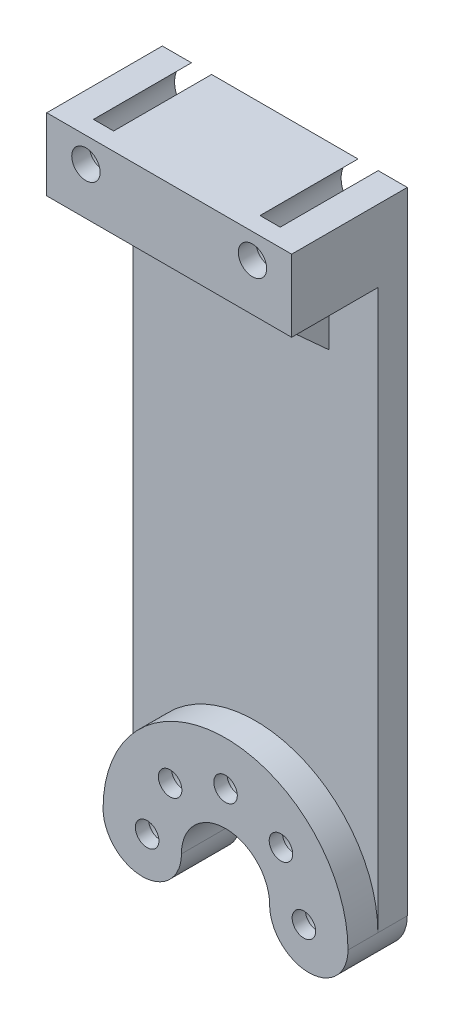
SolidWorks part; units mm, degrees
ref_plane "Plano frontal" through (0, 0, 0) normal (0, 0, 1) x (1, 0, 0)
ref_plane "Plano superior" through (0, 0, 0) normal (0, 1, 0) x (1, 0, 0)
ref_plane "Plano direito" through (0, 0, 0) normal (1, 0, 0) x (0, 0, -1)
sketch "Esboço1" plane through (0, 0, 0) normal (0, 0, 1) x (1, 0, 0)
  arc A0 (4.5, 0) -> (-4.5, 0) centre (0, 0) ccw
  arc A1 (12.5, 0) -> (-12.5, 0) centre (0, 0) ccw
  arc A2 (12.5, 0) -> (4.5, 0) centre (8.5, 0) cw
  arc A3 (-4.5, 0) -> (-12.5, 0) centre (-8.5, 0) cw
  arc A4 (4, 0) -> (-4, 0) centre (0, 0) ccw construction
  circle A6 centre (8.5, 61.8383) radius 1.35 construction
  dimension "D1" = 0.5
  dimension "D2" = 4
extrude "Ressalto-extrusão1" add sketch "Esboço1" against normal offset from surface (3.05 mm away) 2
sketch "Esboço2" plane through (0, 0, -3.05) normal (0, 0, -1) x (-1, 0, 0)
  line L1 (-12.5, 64.3883) -> (12.5, 64.3883)
  line L3 (9.2, 64.6383) -> (-9.2, 64.6383) construction
  line L6 (-12.5, 64.3883) -> (-12.5, 0)
  line L9 (12.5, 64.3883) -> (12.5, 0)
  arc A6 (4.5, 0) -> (12.5, 0) centre (8.5, 0) ccw construction
  arc A7 (-12.5, 0) -> (-4.5, 0) centre (-8.5, 0) ccw construction
  arc A8 (4.5, 0) -> (12.5, 0) centre (8.5, 0) ccw
  arc A9 (-12.5, 0) -> (-4.5, 0) centre (-8.5, 0) ccw
  arc A13 (4.5, 0) -> (-4.5, 0) centre (0, 0) ccw construction
  arc A16 (4.5, 0) -> (-4.5, 0) centre (0, 0) ccw
  dimension "D3" = 0.25
extrude "Ressalto-extrusão2" add sketch "Esboço2" along normal blind 3
sketch "Esboço4" plane through (0, 0, -6.05) normal (0, 0, -1) x (-1, 0, 0)
  line L1 (-12.5, 64.3883) -> (12.5, 64.3883)
  line L2 (-12.5, 64.3883) -> (-12.5, 57.0383)
  line L3 (-12.5, 57.0383) -> (12.5, 57.0383)
  line L4 (12.5, 64.3883) -> (12.5, 57.0383)
  line L5 (12.5, 0) -> (12.5, 64.3883) construction
  line L6 (-12.7, 59.0383) -> (12.7, 59.0383) construction
  dimension "D1" = 2
extrude "Ressalto-extrusão3" add sketch "Esboço4" against normal up to surface (11.8 mm away)
hole_wizard "Rebaixo para SHCS M2.51" positions "Sketch1" profile "Sketch2" counterbore size "M2.5" standard "Ansi Metric" end condition up to next
sketch "Sketch1" plane through (0, 0, -6.05) normal (0, 0, -1) x (-1, 0, 0)
  circle A0 centre (-8.5, 61.8383) radius 1.35 construction
  circle A1 centre (8.5, 61.8383) radius 1.35 construction
  point P0 (-8.5, 61.8383)
  point P3 (8.5, 61.8383)
sketch "Sketch2" plane through (8.5, 61.8383, -6.05) normal (1, 0, 0) x (0, 1, 0)
  line L0 (0, 0) -> (0, 11.8)
  line L1 (0, 11.8) -> (1.45, 11.8)
  line L3 (1.45, 11.8) -> (1.45, 10)
  line L4 (1.45, 10) -> (2.75, 10)
  line L5 (2.75, 10) -> (2.75, 0)
  line L7 (2.75, 0) -> (0, 0)
  line L11 (0, -6.35) -> (0, 107.95) construction
  dimension "Thru Hole Dia." = 2.9
  dimension "Thru Hole Depth" = 11.8
  dimension "C'Bore Dia." = 5.5
  dimension "C'Bore Depth" = 10
hole_wizard "Rebaixo para SHCS M21" positions "Sketch3" profile "Sketch4" counterbore size "M2" standard "Ansi Metric" end condition up to next
sketch "Sketch3" plane through (0, 0, -6.05) normal (0, 0, -1) x (-1, 0, 0)
  line L0 (0, 0) -> (-8, 0) construction
  line L1 (0, 0) -> (-5.6569, 5.6569) construction
  line L2 (0, 0) -> (0, 8) construction
  line L3 (0, 0) -> (5.6569, 5.6569) construction
  line L4 (0, 0) -> (8, 0) construction
  arc A0 (-8.8, 0) -> (-7.2, 0) centre (-8, 0) ccw construction
  point P0 (-8, 0)
  point P15 (-5.6569, 5.6569)
  point P17 (0, 8)
  point P19 (5.6569, 5.6569)
  point P21 (8, 0)
  dimension "D1" = 5
sketch "Sketch4" plane through (8, 0, -6.05) normal (1, 0, 0) x (0, 1, 0)
  line L0 (0, 0) -> (0, 6.05)
  line L1 (0, 6.05) -> (1.2, 6.05)
  line L3 (1.2, 6.05) -> (1.2, 4.7)
  line L4 (1.2, 4.7) -> (2.2, 4.7)
  line L5 (2.2, 4.7) -> (2.2, 0)
  line L7 (2.2, 0) -> (0, 0)
  line L11 (0, -6.35) -> (0, 107.95) construction
  dimension "Thru Hole Dia." = 2.4
  dimension "Thru Hole Depth" = 6.05
  dimension "C'Bore Dia." = 4.4
  dimension "C'Bore Depth" = 4.7
sketch "Esboço5" plane through (0, 0, 0) normal (1, 0, 0) x (0, 0, -1)
  line L0 (-5.75, 57.0383) -> (3.05, 49.0383)
  line L1 (3.05, 57.0383) -> (3.05, 0) construction
  line L2 (-5.75, 57.0383) -> (3.05, 57.0383) construction
  dimension "D1" = 8
rib "Nervura1" sketch "Esboço5" sketch "Esboço5" thickness 15 extrusion direction parallel to sketch draft on no parameters "D1"=15
sketch "Esboço6" plane through (0, 0, -3.05) normal (0, 0, 1) x (1, 0, 0)
  line L0 (7.5, 49.0383) -> (-7.5, 49.0383) construction
  line L1 (4.4016, 49.0383) -> (-4.5372, 49.0383)
  line L2 (4.4016, 49.0383) -> (4.4016, 57.0383)
  line L3 (4.4016, 57.0383) -> (-4.5372, 57.0383)
  line L4 (-4.5372, 49.0383) -> (-4.5372, 57.0383)
  line L5 (4.4251, 52.1001) -> (4.4021, 49.1002) construction
  line L6 (-7.5, 57.0383) -> (7.5, 57.0383) construction
  line L7 (-4.5976, 49.1693) -> (-4.5746, 52.1692) construction
extrude "Corte-extrusão1" cut sketch "Esboço6" along normal up to next
